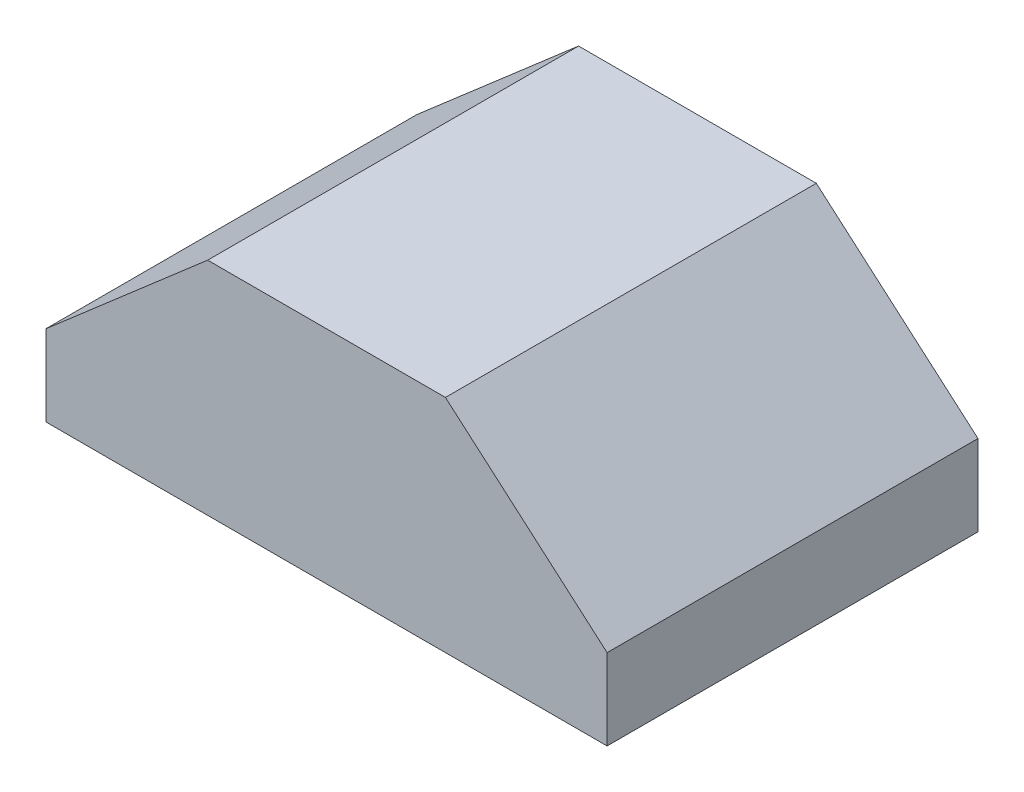
SolidWorks part; units mm, degrees
ref_plane "Plan de face" through (0, 0, 0) normal (0, 0, 1) x (1, 0, 0)
ref_plane "Plan de dessus" through (0, 0, 0) normal (0, 1, 0) x (1, 0, 0)
ref_plane "Plan de droite" through (0, 0, 0) normal (1, 0, 0) x (0, 0, -1)
sketch "Esquisse1" plane through (0, 0, 0) normal (0, 0, 1) x (1, 0, 0)
  line L0 (0, 0) -> (0, 39.8972) construction
  line L1 (-1250, 2323.9403) -> (1250, 2323.9403)
  line L2 (1250, 2323.9403) -> (2950, 850)
  line L3 (2950, 850) -> (2950, 0)
  line L4 (2950, 0) -> (-2950, 0)
  line L5 (-2950, 850) -> (-2950, 0)
  line L6 (-1250, 2323.9403) -> (-2950, 850)
  point P10 (0, 2323.9403)
  dimension "D1" = 5900
  dimension "D2" = 2500
  dimension "D3" = 2250
  dimension "D4" = 850
extrude "Boss.-Extru.1" add sketch "Esquisse1" along normal blind 3900
